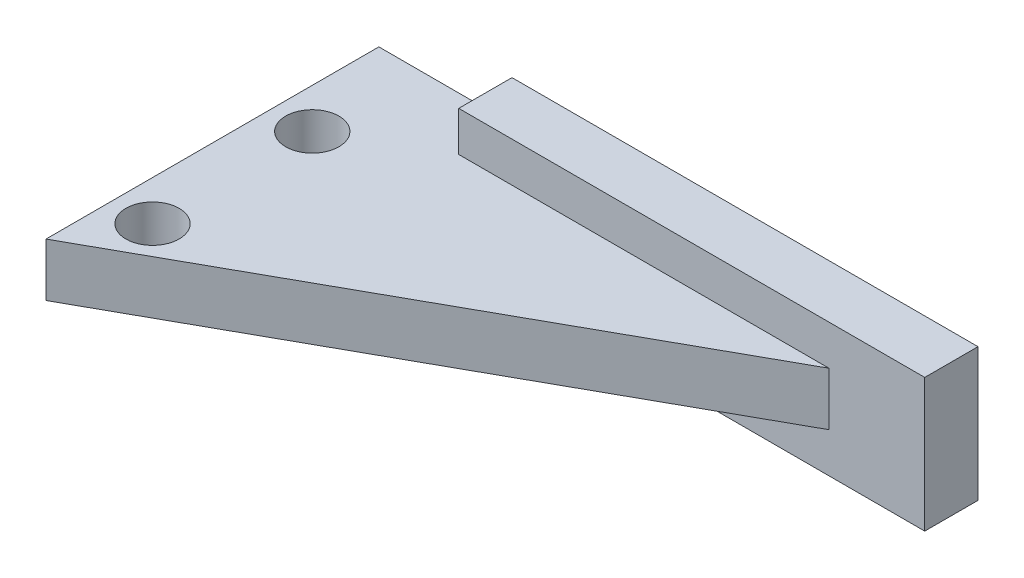
SolidWorks part; units mm, degrees
ref_plane "Plan de face" through (0, 0, 0) normal (0, 0, 1) x (1, 0, 0)
ref_plane "Plan de dessus" through (0, 0, 0) normal (0, 1, 0) x (1, 0, 0)
ref_plane "Plan de droite" through (0, 0, 0) normal (1, 0, 0) x (0, 0, -1)
sketch "Esquisse1" plane through (0, 0, 0) normal (0, 1, 0) x (1, 0, 0)
  line L0 (0, 0) -> (45, 25)
  line L1 (45, 25) -> (0, 25)
  line L2 (0, 25) -> (0, 0)
  dimension "D1" = 25
  dimension "D2" = 45
extrude "Boss.-Extru.1" add sketch "Esquisse1" along normal blind 4
sketch "Esquisse2" plane through (0, 4, 0) normal (0, 1, 0) x (1, 0, 0)
  line L0 (0, 25) -> (0, 0) construction
  line L1 (45, 25) -> (0, 25) construction
  circle A0 centre (3, 17) radius 2
  circle A1 centre (3, 5) radius 2
  point P10 (-1.4575, 21.523)
  point P11 (3.5064, 17.2923)
  dimension "D1" = 4
  dimension "D2" = 4
  dimension "D5" = 8
  dimension "D3" = 3
  dimension "D4" = 3
  dimension "D6" = 12
extrude "Enlèv. mat.-Extru.1" cut sketch "Esquisse2" against normal blind 4
sketch "Esquisse4" plane through (0, 0, -25) normal (0, 0, -1) x (-1, 0, 0)
  line L0 (-45, 4) -> (0, 4) construction
  line L1 (-45, 7) -> (-10, 7)
  line L2 (-45, 7) -> (-45, -3)
  line L3 (-45, -3) -> (-10, -3)
  line L4 (-10, 7) -> (-10, -3)
  line L5 (-45, 0) -> (0, 0) construction
  line L6 (-45, 4) -> (-45, 0) construction
  line L7 (0, 4) -> (0, 0) construction
  dimension "D1" = 3
  dimension "D2" = 3
  dimension "D3" = 0
  dimension "D4" = 10
extrude "Boss.-Extru.2" add sketch "Esquisse4" against normal blind 4
